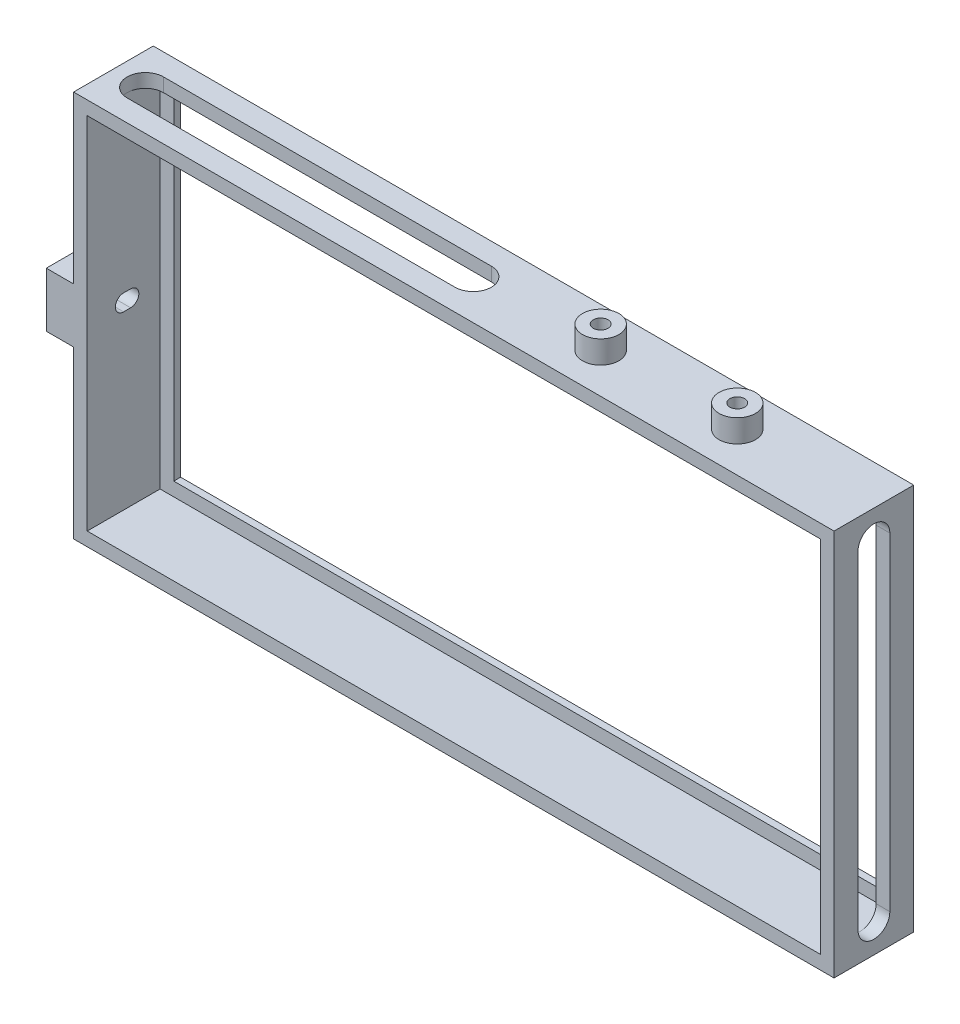
SolidWorks part; units mm, degrees
ref_plane "Front Plane" through (0, 0, 0) normal (0, 0, 1) x (1, 0, 0)
ref_plane "Top Plane" through (0, 0, 0) normal (0, 1, 0) x (1, 0, 0)
ref_plane "Right Plane" through (0, 0, 0) normal (1, 0, 0) x (0, 0, -1)
sketch "Sketch1" plane through (0, 0, 0) normal (0, 0, 1) x (1, 0, 0)
  line L1 (0, 0) -> (167, 0)
  line L2 (0, 0) -> (0, 85)
  line L3 (0, 85) -> (167, 85)
  line L4 (167, 0) -> (167, 85)
  line L5 (6, 6) -> (161, 6)
  line L6 (6, 6) -> (6, 79)
  line L7 (6, 79) -> (161, 79)
  line L8 (161, 6) -> (161, 79)
  dimension "D1" = 85
  dimension "D2" = 167
  dimension "D3" = 6
  dimension "D4" = 6
  dimension "D5" = 6
  dimension "D6" = 6
extrude "Boss-Extrude1" add sketch "Sketch1" along normal blind 1.5
sketch "Sketch2" plane through (0, 0, 1.5) normal (0, 0, 1) x (1, 0, 0)
  line L4 (0, 85) -> (0, 0)
  line L5 (0, 0) -> (167, 0)
  line L6 (167, 0) -> (167, 85)
  line L7 (167, 85) -> (0, 85)
  line L8 (0, 85) -> (0, 0)
  line L9 (0, 0) -> (167, 0)
  line L10 (167, 0) -> (167, 85)
  line L11 (167, 85) -> (0, 85)
  dimension "D1" = 0
extrude "Extrude-Thin1" add sketch "Sketch2" along normal blind 16 thin thin type one direction reverse wall 3
sketch "Sketch3" plane through (0, 0, 0) normal (-1, 0, 0) x (0, 0, 1)
  line L0 (7.975, 42.5) -> (9.525, 42.5) construction
  line L1 (7.975, 44.3) -> (9.525, 44.3)
  line L2 (7.975, 40.7) -> (9.525, 40.7)
  line L3 (17.5, 85) -> (0, 85) construction
  line L4 (17.5, 85) -> (17.5, 0) construction
  arc A0 (7.975, 44.3) -> (7.975, 40.7) centre (7.975, 42.5) ccw
  arc A1 (9.525, 40.7) -> (9.525, 44.3) centre (9.525, 42.5) ccw
  point P2 (8.75, 42.5)
  point P7 (0, 0)
  point P8 (0, 0)
  point P11 (8.75, 85)
  point P12 (0, 0)
  point P15 (17.5, 42.5)
  dimension "D2" = 5.15
  dimension "D1" = 3.6
extrude "Cut-Extrude1" cut sketch "Sketch3" against normal up to next
sketch "Sketch4" plane through (0, 0, 0) normal (-1, 0, 0) x (0, 0, 1)
  line L0 (9.525, 44.3) -> (7.975, 44.3) construction
  line L1 (7.975, 40.7) -> (9.525, 40.7) construction
  line L2 (9.525, 44.3) -> (7.975, 44.3)
  line L3 (7.975, 40.7) -> (9.525, 40.7)
  line L4 (0, 85) -> (0, 0) construction
  line L5 (0, 48.5) -> (17.5, 48.5)
  line L6 (0, 48.5) -> (0, 36.5)
  line L7 (0, 36.5) -> (17.5, 36.5)
  line L8 (17.5, 48.5) -> (17.5, 36.5)
  line L9 (17.5, 85) -> (17.5, 0) construction
  arc A0 (7.975, 44.3) -> (7.975, 40.7) centre (7.975, 42.5) ccw construction
  arc A1 (9.525, 40.7) -> (9.525, 44.3) centre (9.525, 42.5) ccw construction
  arc A2 (7.975, 44.3) -> (7.975, 40.7) centre (7.975, 42.5) ccw
  arc A3 (9.525, 40.7) -> (9.525, 44.3) centre (9.525, 42.5) ccw
  point P14 (17.5, 42.5)
  dimension "D1" = 12
extrude "Boss-Extrude2" add sketch "Sketch4" along normal blind 6
sketch "Sketch5" plane through (-6, 0, 0) normal (-1, 0, 0) x (0, 0, 1)
  line L0 (9.525, 44.3) -> (7.975, 44.3) construction
  circle A0 centre (8.75, 42.5) radius 2.575
  arc A1 (9.525, 40.7) -> (9.525, 44.3) centre (9.525, 42.5) ccw construction
  point P2 (0, 0)
  point P5 (8.75, 44.3)
  point P9 (11.325, 42.5)
extrude "Cut-Extrude2" cut sketch "Sketch5" against normal blind 2.5
sketch "Sketch6" plane through (0, 36.5, 0) normal (0, -1, 0) x (1, 0, 0)
  line L3 (0, 0) -> (0, 17.5) construction
  line L4 (-3.5, 7.975) -> (-3.5, 9.525) construction
  circle A0 centre (-2, 8.75) radius 1.25
  point P4 (0, 0)
  point P7 (-3.5, 8.75)
  dimension "D1" = 2.5
  dimension "D2" = 0.75
extrude "Cut-Extrude6" cut sketch "Sketch6" against normal up to surface (12 mm away) up to face at (-3, 48.5, 8.75)
sketch "Sketch7" plane through (0, 48.5, 0) normal (0, 1, 0) x (1, 0, 0)
  line L0 (-2, -6.25) -> (0, -6.25)
  line L1 (0, -17.5) -> (0, 0) construction
  line L2 (0, -6.25) -> (0, -11.25)
  line L3 (0, -11.25) -> (-2, -11.25)
  circle A0 centre (-2, -8.75) radius 1.5
  arc A1 (-2, -6.25) -> (-2, -11.25) centre (-2, -8.75) ccw
  dimension "D1" = 3
  dimension "D2" = 5
extrude "Boss-Extrude3" add sketch "Sketch7" along normal blind 3
ref_plane "Plane1" through (0, 42.5, 0) normal (0, 1, 0) x (1, 0, 0)
mirror "Mirror1" about plane through (0, 42.5, 0) normal (0, 1, 0) of "Boss-Extrude3"
sketch "Sketch8" plane through (0, 85, 0) normal (0, 1, 0) x (1, 0, 0)
  line L0 (7, -8.75) -> (79, -8.75) construction
  line L1 (7, -4.75) -> (79, -4.75)
  line L2 (7, -12.75) -> (79, -12.75)
  line L3 (0, -17.5) -> (0, 0) construction
  line L4 (167, -17.5) -> (167, 0) construction
  arc A0 (7, -4.75) -> (7, -12.75) centre (7, -8.75) ccw
  arc A1 (79, -12.75) -> (79, -4.75) centre (79, -8.75) ccw
  circle A2 centre (107, -8.75) radius 1.625
  circle A3 centre (137, -8.75) radius 1.625
  point P2 (43, -8.75)
  point P9 (0, -8.75)
  point P14 (0, 0)
  point P17 (137, -8.75)
  point P18 (137, -8.75)
  dimension "D2" = 3
  dimension "D3" = 80
  dimension "D6" = 3.25
  dimension "D1" = 8
  dimension "D4" = 30
  dimension "D5" = 30
extrude "Cut-Extrude7" cut sketch "Sketch8" against normal up to next
sketch "Sketch9" plane through (0, 85, 0) normal (0, 1, 0) x (1, 0, 0)
  circle A0 centre (137, -8.75) radius 1.625 construction
  circle A1 centre (107, -8.75) radius 1.625 construction
  circle A2 centre (137, -8.75) radius 1.625
  circle A3 centre (107, -8.75) radius 1.625
  circle A4 centre (107, -8.75) radius 4
  circle A5 centre (137, -8.75) radius 4
  dimension "D1" = 8
extrude "Boss-Extrude4" add sketch "Sketch9" along normal blind 5
sketch "Sketch10" plane through (167, 0, 0) normal (1, 0, 0) x (0, 0, -1)
  line L0 (-8.75, 78.5) -> (-8.75, 6.5) construction
  line L1 (-5.25, 78.5) -> (-5.25, 6.5)
  line L2 (-12.25, 78.5) -> (-12.25, 6.5)
  line L3 (-17.5, 85) -> (0, 85) construction
  line L6 (-17.5, 0) -> (0, 0) construction
  arc A0 (-5.25, 78.5) -> (-12.25, 78.5) centre (-8.75, 78.5) ccw
  arc A1 (-12.25, 6.5) -> (-5.25, 6.5) centre (-8.75, 6.5) ccw
  point P2 (-8.75, 42.5)
  point P7 (-8.75, 82)
  point P12 (0, 0)
  point P13 (-8.75, 0)
  dimension "D2" = 3
  dimension "D1" = 3
  dimension "D3" = 7
extrude "Cut-Extrude8" cut sketch "Sketch10" against normal up to next
